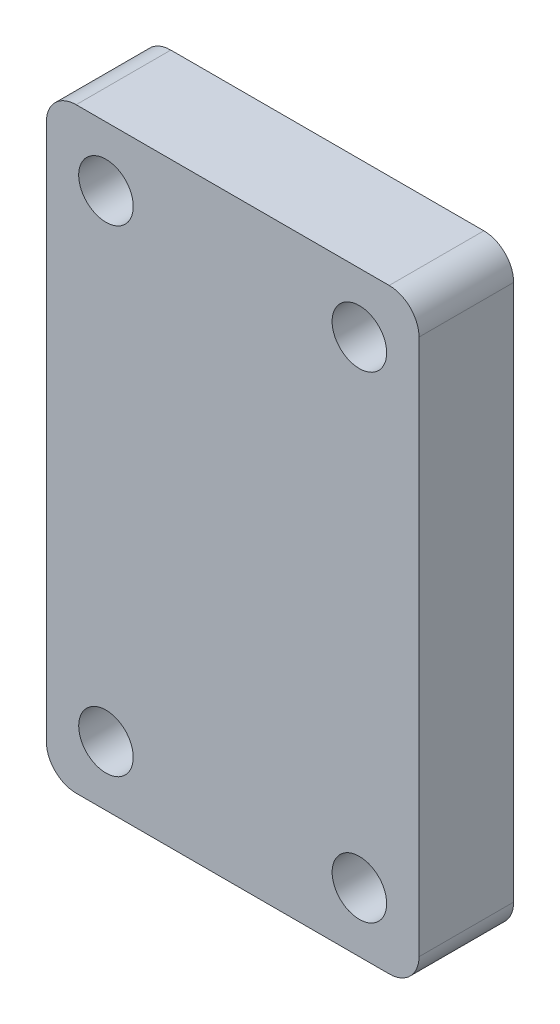
SolidWorks part; units mm, degrees
material "ABS"
ref_plane "Plan de face" through (0, 0, 0) normal (0, 0, 1) x (1, 0, 0)
ref_plane "Plan de dessus" through (0, 0, 0) normal (0, 1, 0) x (1, 0, 0)
ref_plane "Plan de droite" through (0, 0, 0) normal (1, 0, 0) x (0, 0, -1)
sketch "Esquisse1" plane through (0, 0, 0) normal (0, 0, 1) x (1, 0, 0)
  line L1 (-12.5, 20) -> (12.5, 20)
  line L2 (-12.5, 20) -> (-12.5, -20)
  line L3 (-12.5, -20) -> (12.5, -20)
  line L4 (12.5, 20) -> (12.5, -20)
  point P4 (-12.5, 0)
  point P6 (0, 20)
  dimension "D1" = 25
  dimension "D2" = 40
extrude "Boss.-Extru.1" add sketch "Esquisse1" along normal mid plane 6.35
sketch "Esquisse2" plane through (0, 0, 3.175) normal (0, 0, 1) x (1, 0, 0)
  line L0 (0, -3.4925) -> (0, 3.4925) construction
  line L1 (3.4925, 0) -> (-3.4925, 0) construction
  line L2 (12.5, 20) -> (-12.5, 20) construction
  line L3 (-12.5, 20) -> (-12.5, -20) construction
  circle A0 centre (-8.5, 16) radius 1.83
  circle A1 centre (8.5, 16) radius 1.83
  circle A2 centre (8.5, -16) radius 1.83
  circle A3 centre (-8.5, -16) radius 1.83
  dimension "D1" = 3.66
  dimension "D2" = 4
  dimension "D3" = 4
extrude "Enlèv. mat.-Extru.1" cut sketch "Esquisse2" against normal up to next
fillet "Congé1" radius 2 4 edges at (-12.5, -20, 0) (12.5, -20, 0) (-12.5, 20, 0) (12.5, 20, 0)
